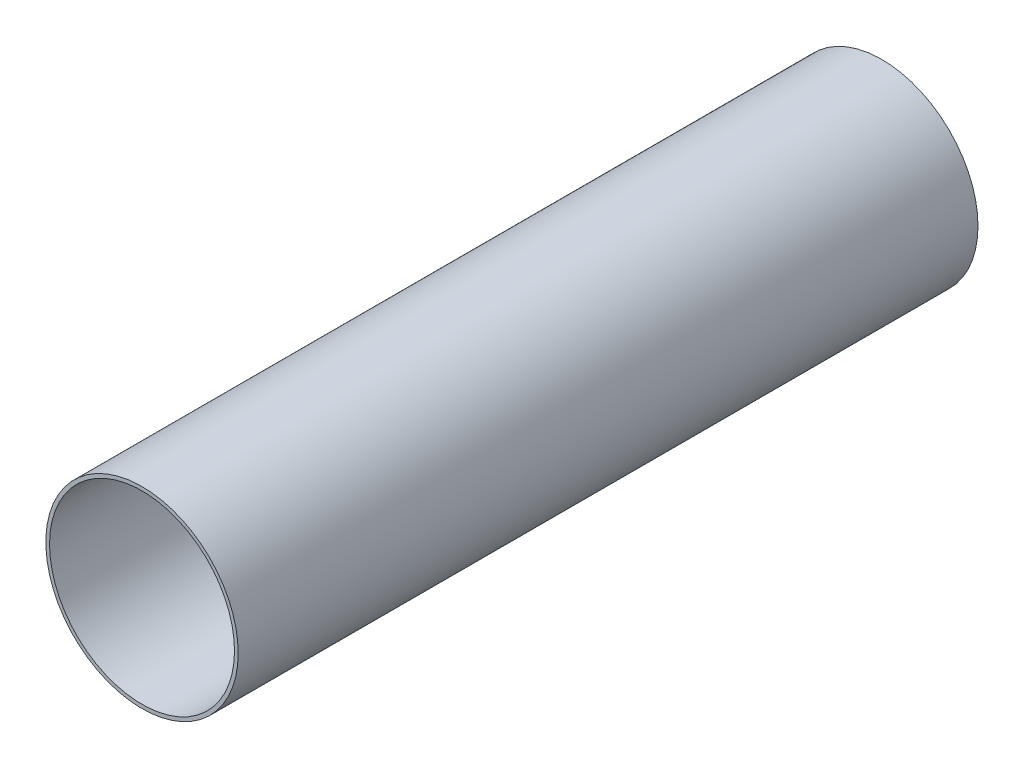
SolidWorks part; units mm, degrees
ref_plane "Face" through (0, 0, 0) normal (0, 0, 1) x (1, 0, 0)
ref_plane "Dessus" through (0, 0, 0) normal (0, 1, 0) x (1, 0, 0)
ref_plane "Droite" through (0, 0, 0) normal (1, 0, 0) x (0, 0, -1)
sketch "Esquisse1" plane through (0, 0, 0) normal (0, 0, 1) x (1, 0, 0)
  circle A0 centre (0, 0) radius 25
  circle A1 centre (0, 0) radius 26
  dimension "D1" = 1
extrude "Boss.-Extru.1" add sketch "Esquisse1" along normal blind 200
